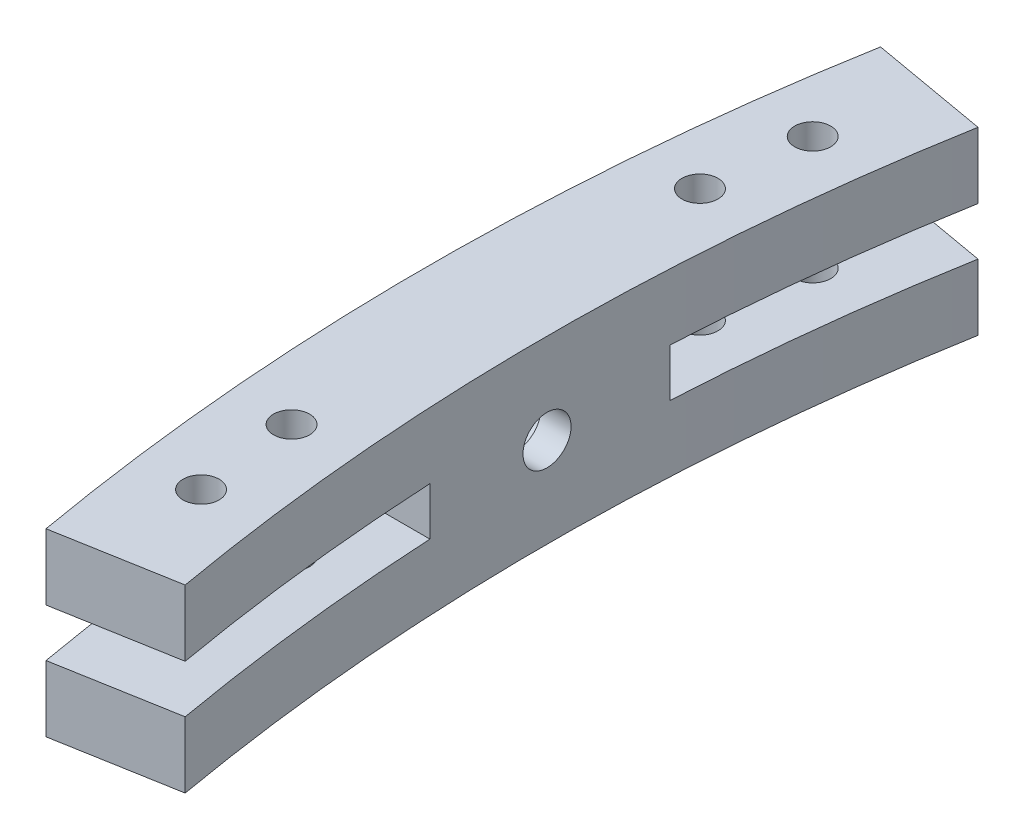
SolidWorks part; units mm, degrees
ref_plane "Front Plane" through (0, 0, 0) normal (0, 0, 1) x (1, 0, 0)
ref_plane "Top Plane" through (0, 0, 0) normal (0, 1, 0) x (1, 0, 0)
ref_plane "Right Plane" through (0, 0, 0) normal (1, 0, 0) x (0, 0, -1)
sketch "Sketch1" plane through (0, 0, 0) normal (0, 0, 1) x (1, 0, 0)
  line L0 (190, 0) -> (-190, 0) construction
  line L1 (0, 190) -> (0, -190) construction
  line L2 (0, 0) -> (-187.1135, 32.9932) construction
  line L3 (0, 0) -> (-187.1135, -32.9932) construction
  line L4 (-187.1135, 32.9932) -> (-196.9616, 34.7296)
  line L5 (-187.1135, -32.9932) -> (-196.9616, -34.7296)
  arc A0 (-187.1135, 32.9932) -> (-187.1135, -32.9932) centre (0, 0) ccw
  arc A1 (-196.9616, 34.7296) -> (-196.9616, -34.7296) centre (0, 0) ccw
  circle A3 centre (0, 0) radius 190 construction
  dimension "D1" = 380
  dimension "D2" = 10
  dimension "D3" = 20
sketch "Sketch9" plane through (0, 0, 0) normal (0, 1, 0) x (1, 0, 0)
  line L0 (0, 0) -> (-196.9616, 34.7296)
  line L1 (-200, 0) -> (200, 0) construction
  line L2 (0, 0) -> (-196.9616, -34.7296)
  circle A0 centre (0, 0) radius 195 construction
  circle A1 centre (0, 0) radius 195 construction
  circle A8 centre (0, 0) radius 200 construction
  circle A9 centre (0, 0) radius 190 construction
  circle A10 centre (0, 0) radius 200
  circle A11 centre (0, 0) radius 190
  dimension "D1" = 20
extrude "base" add sketch "Sketch9" along normal mid plane 15 contours A11 L0 A10 L2
sketch "Sketch11" plane through (0, 0, 0) normal (0, 1, 0) x (1, 0, 0)
  line L8 (-189.7367, -10) -> (-199.7498, -10) construction
  line L9 (-187.1135, -32.9932) -> (-196.9616, -34.7296) construction
  line L10 (-189.7367, 10) -> (-199.7498, 10) construction
  line L11 (-187.1135, 32.9932) -> (-196.9616, 34.7296) construction
  line L12 (-189.7367, -10) -> (-199.7498, -10)
  line L13 (-187.1135, -32.9932) -> (-196.9616, -34.7296)
  line L14 (-189.7367, 10) -> (-199.7498, 10)
  line L15 (-187.1135, 32.9932) -> (-196.9616, 34.7296)
  circle A14 centre (0, 0) radius 200 construction
  circle A15 centre (0, 0) radius 190 construction
  arc A16 (-196.9616, 34.7296) -> (-199.7498, 10) centre (0, 0) ccw
  arc A17 (-187.1135, 32.9932) -> (-189.7367, 10) centre (0, 0) ccw
  arc A18 (-199.7498, -10) -> (-196.9616, -34.7296) centre (0, 0) ccw
  arc A19 (-189.7367, -10) -> (-187.1135, -32.9932) centre (0, 0) ccw
extrude "mount" cut sketch "Sketch11" along normal up to surface and the other way up to surface
sketch "Sketch12" plane through (0, 0, 0) normal (0, 1, 0) x (1, 0, 0)
  line L0 (-200, 0) -> (200, 0) construction
  line L1 (-200, 0) -> (200, 0) construction
  line L2 (0, 0) -> (-193.3317, 25.4526) construction
  line L3 (0, 0) -> (-194.258, 16.9954) construction
  line L4 (0, 0) -> (-194.258, -16.9954) construction
  line L5 (0, 0) -> (-193.3317, -25.4526) construction
  circle A0 centre (0, 0) radius 195 construction
  circle A1 centre (0, 0) radius 195 construction
  circle A2 centre (-193.3317, 25.4526) radius 1.5
  circle A3 centre (-194.258, 16.9954) radius 1.5
  circle A4 centre (-194.258, -16.9954) radius 1.5
  circle A5 centre (-193.3317, -25.4526) radius 1.5
  dimension "D1" = 3
  dimension "D2" = 10
  dimension "D3" = 15
extrude "mount hole" cut sketch "Sketch12" against normal through all both and the other way through all
sketch "Sketch13" plane through (0, 0, 0) normal (0, 1, 0) x (1, 0, 0)
  line L0 (0, 0) -> (-195, 0) construction
  line L1 (-200, 0) -> (200, 0) construction
  line L2 (-195, 0) -> (-195, 3.5)
  line L7 (-195, 0) -> (-192.5, 0)
  line L17 (-195, 3.5) -> (-192.5, 3.5)
  line L18 (-192.5, 3.5) -> (-192.5, 0)
  circle A0 centre (0, 0) radius 195 construction
  dimension "D1" = 7
  dimension "D3" = 2.5
ref_plane "shaft" through (-195, 0, 0) normal (-1, 0, 0) x (0, 0, 1)
sketch "Sketch14" plane through (-195, 0, 0) normal (-1, 0, 0) x (0, 0, 1)
  circle A0 centre (0, 0) radius 2
  dimension "D1" = 4
extrude "shaft hole" cut sketch "Sketch14" against normal through all
revolve "Cut-Revolve1" cut sketch "Sketch13" angle 360 about L0
